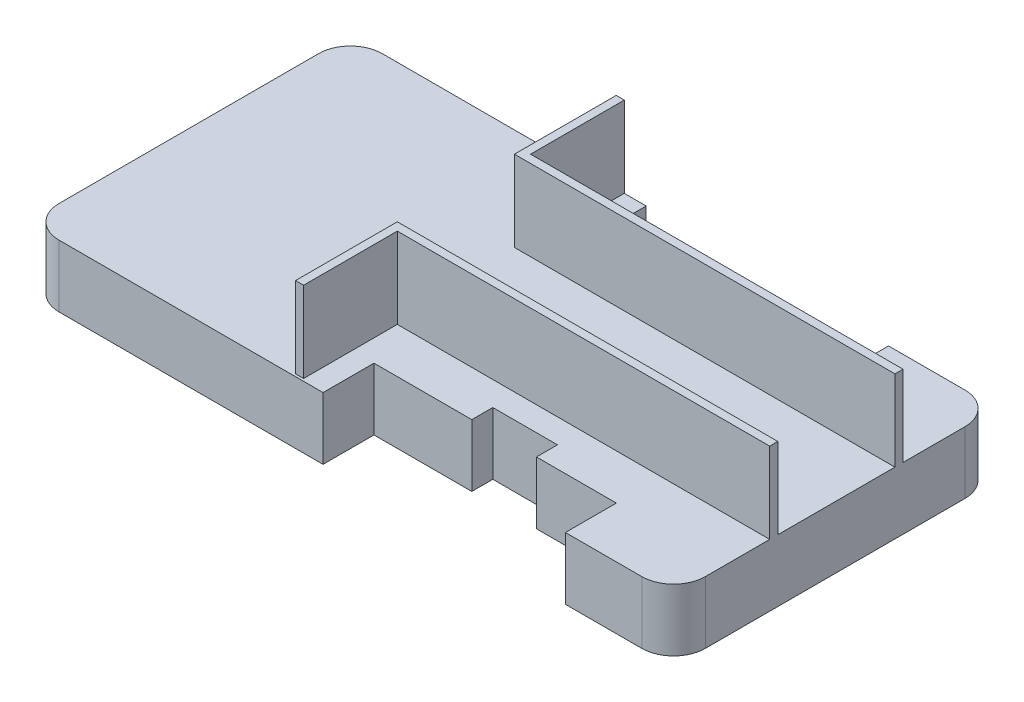
SolidWorks part; units mm, degrees
ref_plane "Front Plane" through (0, 0, 0) normal (0, 0, 1) x (1, 0, 0)
ref_plane "Top Plane" through (0, 0, 0) normal (0, 1, 0) x (1, 0, 0)
ref_plane "Right Plane" through (0, 0, 0) normal (1, 0, 0) x (0, 0, -1)
sketch "Sketch2" plane through (-97.4825, 0, 34.7351) normal (0, 1, 0) x (1, 0, 0)
  line L1 (-121.146, 85.1479) -> (82.054, 85.1479)
  line L2 (-121.146, 85.1479) -> (-121.146, -16.4521)
  line L3 (-121.146, -16.4521) -> (82.054, -16.4521)
  line L4 (82.054, 85.1479) -> (82.054, -16.4521)
  dimension "D1" = 203.2
  dimension "D2" = 101.6
extrude "Boss-Extrude1" add sketch "Sketch2" along normal blind 19.558 contours L2 L1 L4 L3
sketch "Sketch3" plane through (-97.4825, 19.558, 34.7351) normal (0, 1, 0) x (1, 0, 0)
  line L0 (-28.1554, 85.1479) -> (-28.1554, 69.9079)
  line L1 (-121.146, 85.1479) -> (82.054, 85.1479) construction
  line L2 (-28.1554, 69.9079) -> (-15.0152, 69.9079)
  line L3 (-15.0152, 69.9079) -> (2.6044, 69.9079)
  line L4 (2.6044, 69.9079) -> (2.6044, 63.3039)
  line L5 (2.6044, 63.3039) -> (22.9244, 63.3039)
  line L6 (22.9244, 63.3039) -> (22.9244, 69.9079)
  line L7 (22.9244, 69.9079) -> (48.0446, 69.9079)
  line L8 (48.0446, 69.9079) -> (48.0446, 85.1479)
  line L9 (48.0446, 85.1479) -> (48.0446, 90.2279)
  line L10 (48.0446, 90.2279) -> (-28.1554, 90.2279)
  line L11 (-28.1554, 90.2279) -> (-28.1554, 85.1479)
  line L12 (48.0446, 90.2279) -> (48.0446, 69.9079)
  line M14 (82.054, 85.1479) -> (-121.146, 85.1479)
  dimension "D1" = 76.2
  dimension "D2" = 15.24
  dimension "D3" = 5.08
  dimension "D4" = 20.32
  dimension "D5" = 6.604
extrude "Cut-Extrude2" cut sketch "Sketch3" against normal blind 19.558 contours L7 L8 L0 L2 L3 L4 L5 L6 M14 | L10 L11 L9 M14
sketch3d "3DSketch1" plane through (0, 0, 0) normal (0, 0, 1) x (1, 0, 0)
mirror "Mirror4" about plane through (0, 0, 0) normal (0, 0, 1) of "Cut-Extrude2"
fillet "Fillet1" radius 10 1 edges at (-15.4285, 9.779, 51.1873)
fillet "Fillet2" radius 10 1 edges at (-218.6285, 9.779, -50.4127)
fillet "Fillet3" radius 10 1 edges at (-218.6285, 9.779, 51.1873)
fillet "Fillet4" radius 10 1 edges at (-15.4285, 9.779, -50.4127)
sketch "Sketch7" plane through (0, 19.558, 0) normal (0, 1, 0) x (1, 0, 0)
  line L1 (-208.6285, 50.4127) -> (-125.6379, 50.4127) construction
  line L3 (-15.4285, 40.4127) -> (-15.4285, -41.1873) construction
  line L4 (-132.5225, 50.4127) -> (-132.5225, 20.9487)
  line L5 (-132.5225, 20.9487) -> (-15.4285, 20.9487)
extrude "Extrude-Thin5" add sketch "Sketch7" along normal blind 25.4 thin
mirror "Mirror5" about plane through (0, 0, 0) normal (0, 0, 1) of "Extrude-Thin5"
